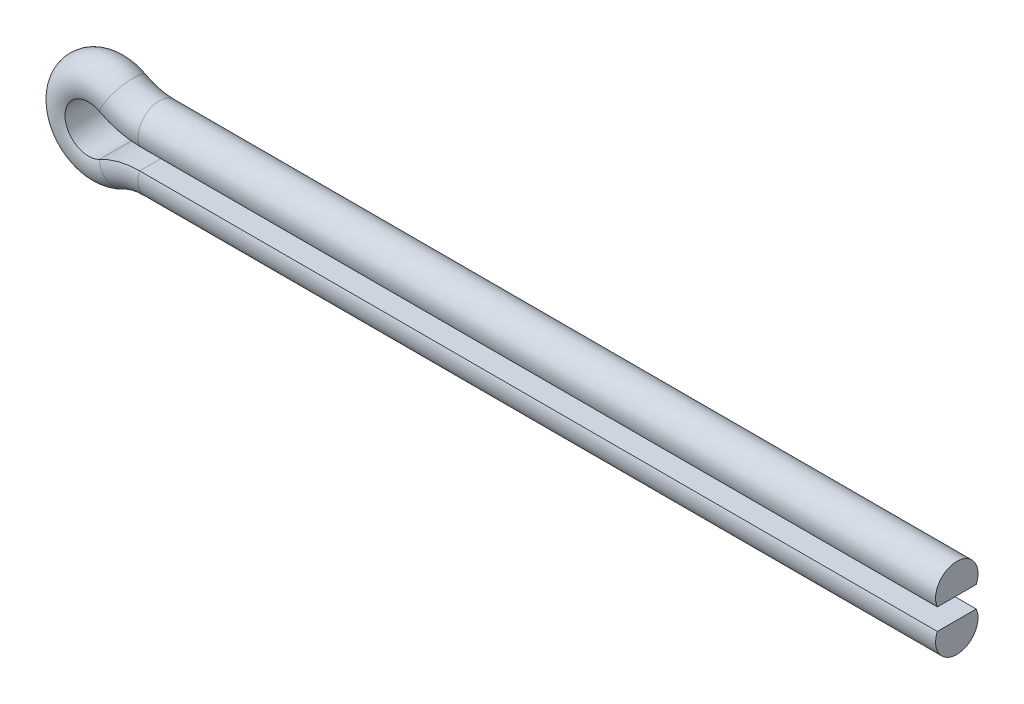
SolidWorks part; units mm, degrees
ref_plane "Front Plane" through (0, 0, 0) normal (0, 0, 1) x (1, 0, 0)
ref_plane "Top Plane" through (0, 0, 0) normal (0, 1, 0) x (1, 0, 0)
ref_plane "Right Plane" through (0, 0, 0) normal (1, 0, 0) x (0, 0, -1)
sketch "Sketch1" plane through (0, 0, 0) normal (0, 0, 1) x (1, 0, 0)
  line L0 (0, 0) -> (104.8676, 0) construction
  line L1 (6.0311, 1.25) -> (100, 1.25)
  line L2 (6.0311, -1.25) -> (100, -1.25)
  arc A0 (1.3063, 2.4366) -> (1.3063, -2.4366) centre (0, 0) ccw
  arc A1 (6.0311, -1.25) -> (1.3063, -2.4366) centre (6.0311, -11.25) ccw
  arc A2 (6.0311, 1.25) -> (1.3063, 2.4366) centre (6.0311, 11.25) cw
  dimension "D1" = 2.5
  dimension "D3" = 10
  dimension "D2" = 100
ref_plane "Plane1" through (100, 1.25, 0) normal (1, 0, 0) x (0, 0, -1)
sketch "Sketch2" plane through (100, 1.25, 0) normal (1, 0, 0) x (0, 0, -1)
  line L0 (0, 1.5147) -> (0, -4.0147) construction
  line L2 (-2.2913, 0.0001) -> (2.2913, 0.0001)
  arc A0 (2.2913, 0.0001) -> (-2.2913, 0.0001) centre (0, 1.0001) ccw
  dimension "D1" = 5
sweep "Sweep1" add profiles "Sketch2" path "Sketch1"
